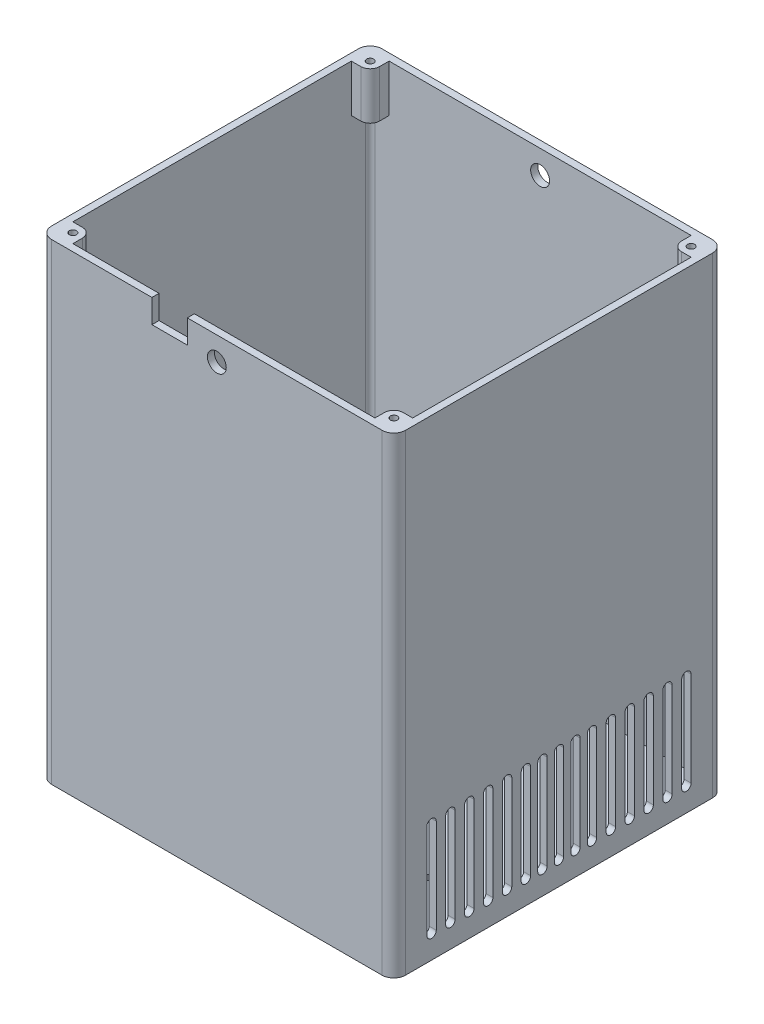
SolidWorks part; units mm, degrees
ref_plane "Front Plane" through (0, 0, 0) normal (0, 0, 1) x (1, 0, 0)
ref_plane "Top Plane" through (0, 0, 0) normal (0, 1, 0) x (1, 0, 0)
ref_plane "Right Plane" through (0, 0, 0) normal (1, 0, 0) x (0, 0, -1)
sketch "Sketch1" plane through (0, 0, 0) normal (0, 1, 0) x (1, 0, 0)
  line L1 (70, -70) -> (-70, -70)
  line L2 (75, -65) -> (75, 65)
  line L3 (70, 70) -> (-70, 70)
  line L4 (-75, -65) -> (-75, 65)
  line L5 (75, -70) -> (-75, 70) construction
  line L6 (75, 70) -> (-75, -70) construction
  arc A0 (-70, -70) -> (-75, -65) centre (-70, -65) cw
  arc A1 (70, -70) -> (75, -65) centre (70, -65) ccw
  arc A2 (75, 65) -> (70, 70) centre (70, 65) ccw
  arc A3 (-70, 70) -> (-75, 65) centre (-70, 65) ccw
  point P0 (0, 0)
  dimension "D3" = 5
  dimension "D1" = 150
  dimension "D2" = 140
extrude "Boss-Extrude1" add sketch "Sketch1" along normal blind 200
shell "Shell1" thickness 3
sketch "Sketch2" plane through (0, 0, 70) normal (0, 0, 1) x (1, 0, 0)
  line L0 (-70, 200) -> (70, 200) construction
  line L1 (-75, 200) -> (-75, 0) construction
  circle A0 centre (0, 190) radius 4
  dimension "D1" = 8
  dimension "D2" = 10
  dimension "D3" = 75
extrude "Cut-Extrude1" cut sketch "Sketch2" against normal through all
sketch "Sketch3" plane through (75, 0, 0) normal (1, 0, 0) x (0, 0, -1)
  line L0 (0, 50) -> (0, 10) construction
  line L1 (2, 50) -> (2, 10)
  line L2 (-2, 50) -> (-2, 10)
  line L3 (-65, 0) -> (65, 0) construction
  line L4 (5, 50) -> (5, 10)
  line L5 (9, 50) -> (9, 10)
  line L6 (7, 50) -> (7, 10) construction
  line L7 (12, 50) -> (12, 10)
  line L8 (16, 50) -> (16, 10)
  line L9 (14, 50) -> (14, 10) construction
  line L10 (-9, 50) -> (-9, 10)
  line L11 (-5, 50) -> (-5, 10)
  line L12 (-7, 50) -> (-7, 10) construction
  line L13 (-16, 50) -> (-16, 10)
  line L14 (-12, 50) -> (-12, 10)
  line L15 (-14, 50) -> (-14, 10) construction
  line L16 (24, 50) -> (24, 10)
  line L17 (20, 50) -> (20, 10)
  line L18 (22, 50) -> (22, 10) construction
  line L19 (32, 50) -> (32, 10)
  line L20 (28, 50) -> (28, 10)
  line L21 (30, 50) -> (30, 10) construction
  line L22 (40, 50) -> (40, 10)
  line L23 (36, 50) -> (36, 10)
  line L24 (38, 50) -> (38, 10) construction
  line L25 (48, 50) -> (48, 10)
  line L26 (44, 50) -> (44, 10)
  line L27 (46, 50) -> (46, 10) construction
  line L28 (56, 50) -> (56, 10)
  line L29 (52, 50) -> (52, 10)
  line L30 (54, 50) -> (54, 10) construction
  line L31 (-22, 50) -> (-22, 10) construction
  line L32 (-20, 50) -> (-20, 10)
  line L33 (-24, 50) -> (-24, 10)
  line L34 (-30, 50) -> (-30, 10) construction
  line L35 (-28, 50) -> (-28, 10)
  line L36 (-32, 50) -> (-32, 10)
  line L37 (-38, 50) -> (-38, 10) construction
  line L38 (-36, 50) -> (-36, 10)
  line L39 (-40, 50) -> (-40, 10)
  line L40 (-46, 50) -> (-46, 10) construction
  line L41 (-44, 50) -> (-44, 10)
  line L42 (-48, 50) -> (-48, 10)
  line L43 (-54, 50) -> (-54, 10) construction
  line L44 (-52, 50) -> (-52, 10)
  line L45 (-56, 50) -> (-56, 10)
  arc A0 (2, 50) -> (-2, 50) centre (0, 50) ccw
  arc A1 (-2, 10) -> (2, 10) centre (0, 10) ccw
  arc A2 (9, 50) -> (5, 50) centre (7, 50) ccw
  arc A3 (5, 10) -> (9, 10) centre (7, 10) ccw
  arc A4 (16, 50) -> (12, 50) centre (14, 50) ccw
  arc A5 (12, 10) -> (16, 10) centre (14, 10) ccw
  arc A6 (-5, 50) -> (-9, 50) centre (-7, 50) ccw
  arc A7 (-9, 10) -> (-5, 10) centre (-7, 10) ccw
  arc A8 (-12, 50) -> (-16, 50) centre (-14, 50) ccw
  arc A9 (-16, 10) -> (-12, 10) centre (-14, 10) ccw
  arc A10 (20, 10) -> (24, 10) centre (22, 10) ccw
  arc A11 (24, 50) -> (20, 50) centre (22, 50) ccw
  arc A12 (28, 10) -> (32, 10) centre (30, 10) ccw
  arc A13 (32, 50) -> (28, 50) centre (30, 50) ccw
  arc A14 (36, 10) -> (40, 10) centre (38, 10) ccw
  arc A15 (40, 50) -> (36, 50) centre (38, 50) ccw
  arc A16 (44, 10) -> (48, 10) centre (46, 10) ccw
  arc A17 (48, 50) -> (44, 50) centre (46, 50) ccw
  arc A18 (52, 10) -> (56, 10) centre (54, 10) ccw
  arc A19 (56, 50) -> (52, 50) centre (54, 50) ccw
  arc A20 (-20, 50) -> (-24, 50) centre (-22, 50) ccw
  arc A21 (-24, 10) -> (-20, 10) centre (-22, 10) ccw
  arc A22 (-28, 50) -> (-32, 50) centre (-30, 50) ccw
  arc A23 (-32, 10) -> (-28, 10) centre (-30, 10) ccw
  arc A24 (-36, 50) -> (-40, 50) centre (-38, 50) ccw
  arc A25 (-40, 10) -> (-36, 10) centre (-38, 10) ccw
  arc A26 (-44, 50) -> (-48, 50) centre (-46, 50) ccw
  arc A27 (-48, 10) -> (-44, 10) centre (-46, 10) ccw
  arc A28 (-52, 50) -> (-56, 50) centre (-54, 50) ccw
  arc A29 (-56, 10) -> (-52, 10) centre (-54, 10) ccw
  point P2 (0, 30)
  point P14 (7, 30)
  point P21 (14, 30)
  point P27 (-7, 30)
  point P34 (-14, 30)
  point P41 (22, 30)
  point P48 (30, 30)
  point P55 (38, 30)
  point P62 (46, 30)
  point P69 (54, 30)
  point P77 (-22, 30)
  point P84 (-30, 30)
  point P91 (-38, 30)
  point P98 (-46, 30)
  point P105 (-54, 30)
  dimension "D3" = 2
  dimension "D1" = 40
  dimension "D2" = 30
  dimension "D6" = 3
  dimension "D7" = 3
  dimension "D4" = 3
  dimension "D5" = 3
  dimension "D8" = 6
  dimension "D9" = 6
extrude "Cut-Extrude2" cut sketch "Sketch3" against normal through all
sketch "Sketch4" plane through (0, 3, 0) normal (0, 1, 0) x (1, 0, 0)
  line L0 (70, 67) -> (-70, 67) construction
  line L1 (-48.7721, -23) -> (-33.7721, -23)
  line L2 (-48.7721, -23) -> (-48.7721, -38)
  line L3 (-48.7721, -38) -> (-33.7721, -38)
  line L4 (-33.7721, -23) -> (-33.7721, -38)
  line L5 (-48.7721, -23) -> (-33.7721, -38) construction
  line L6 (-48.7721, -38) -> (-33.7721, -23) construction
  point P0 (-41.2721, -30.5)
  dimension "D1" = 15
  dimension "D2" = 15
  dimension "D3" = 90
extrude "Cut-Extrude3" cut sketch "Sketch4" against normal through all
sketch "Sketch5" plane through (0, 0, 70) normal (0, 0, 1) x (1, 0, 0)
  line L0 (-70, 200) -> (70, 200) construction
  line L1 (-27.5, 210) -> (-12.5, 210)
  line L2 (-27.5, 210) -> (-27.5, 190)
  line L3 (-27.5, 190) -> (-12.5, 190)
  line L4 (-12.5, 210) -> (-12.5, 190)
  line L5 (-27.5, 210) -> (-12.5, 190) construction
  line L6 (-27.5, 190) -> (-12.5, 210) construction
  point P0 (-20, 200)
  point P7 (0, 200)
  dimension "D1" = 20
  dimension "D2" = 15
  dimension "D3" = 20
extrude "Cut-Extrude4" cut sketch "Sketch5" against normal blind 10
sketch "Sketch6" plane through (0, 3, 0) normal (0, 1, 0) x (1, 0, 0)
  circle A0 centre (11.0255, -27.5994) radius 1.5
  circle A1 centre (11.0255, 23.9006) radius 1.5
  circle A2 centre (46.6255, 23.9006) radius 1.5
  circle A3 centre (46.6255, -27.5994) radius 1.5645
extrude "Cut-Extrude5" cut sketch "Sketch6" against normal through all
sketch "Sketch7" plane through (0, 200, 0) normal (0, 1, 0) x (1, 0, 0)
  line L0 (70, 70) -> (-70, 70) construction
  line L1 (-75, 65) -> (-75, -65) construction
  line L2 (-64, 63) -> (-64, 67)
  line L3 (70, 67) -> (-70, 67) construction
  line L4 (-64, 67) -> (-70, 67)
  line L5 (-72, 65) -> (-72, -65) construction
  line L6 (-72, 65) -> (-72, -65) construction
  line L7 (-72, 65) -> (-72, 59)
  line L8 (-72, 59) -> (-68, 59)
  line L9 (0, 0) -> (0, 50000) construction
  line L10 (0, 0) -> (-50000, 0) construction
  line L11 (72, 65) -> (72, 59)
  line L12 (64, 67) -> (70, 67)
  line L13 (64, 63) -> (64, 67)
  line L14 (72, 59) -> (68, 59)
  line L15 (64, -67) -> (70, -67)
  line L16 (64, -63) -> (64, -67)
  line L17 (72, -59) -> (68, -59)
  line L18 (72, -65) -> (72, -59)
  line L19 (-72, -65) -> (-72, -59)
  line L20 (-64, -67) -> (-70, -67)
  line L21 (-64, -63) -> (-64, -67)
  line L22 (-72, -59) -> (-68, -59)
  arc A1 (-68, 59) -> (-64, 63) centre (-68, 63) ccw
  arc A2 (-70, 67) -> (-72, 65) centre (-70, 65) ccw
  circle A3 centre (-68, 63) radius 1.5
  circle A4 centre (68, 63) radius 1.5
  arc A5 (70, 67) -> (72, 65) centre (70, 65) cw
  arc A6 (68, 59) -> (64, 63) centre (68, 63) cw
  circle A7 centre (68, -63) radius 1.5
  arc A8 (70, -67) -> (72, -65) centre (70, -65) ccw
  arc A9 (68, -59) -> (64, -63) centre (68, -63) ccw
  circle A10 centre (-68, -63) radius 1.5
  arc A11 (-70, -67) -> (-72, -65) centre (-70, -65) cw
  arc A12 (-68, -59) -> (-64, -63) centre (-68, -63) cw
  line M23 (70, -67) -> (-12.5, -67)
  line M37 (-72, -65) -> (-72, 65)
  arc M38 (-72, 65) -> (-70, 67) centre (-70, 65) cw
  line M39 (-70, 67) -> (70, 67)
  arc M40 (70, 67) -> (72, 65) centre (70, 65) cw
  line M41 (72, 65) -> (72, -65)
  arc M42 (72, -65) -> (70, -67) centre (70, -65) cw
  dimension "D1" = 8
  dimension "D4" = 3
  dimension "D2" = 7
  dimension "D3" = 7
extrude "Boss-Extrude2" add sketch "Sketch7" against normal blind 20 contours L8 A1 L2 A3 M39 M38 M37 | A6 L14 L13 A4 M41 M40 M39 | L17 A9 L16 A7 M23 M42 M41 | A10 | L19 L22 A12 L21 L20 A11
sketch "Sketch8" plane through (0, 3, 0) normal (0, 1, 0) x (1, 0, 0)
  line L0 (70, 70) -> (-70, 70) construction
  line L1 (-75, 65) -> (-75, -65) construction
  line L3 (0, 0) -> (0, 50000) construction
  line L4 (0, 0) -> (-50000, 0) construction
  circle A0 centre (-60, 55) radius 1.5
  circle A1 centre (-60, -55) radius 1.5
  circle A2 centre (60, -55) radius 1.5
  circle A3 centre (60, 55) radius 1.5
  dimension "D1" = 3
  dimension "D2" = 15
  dimension "D3" = 15
extrude "Cut-Extrude6" cut sketch "Sketch8" against normal through all
